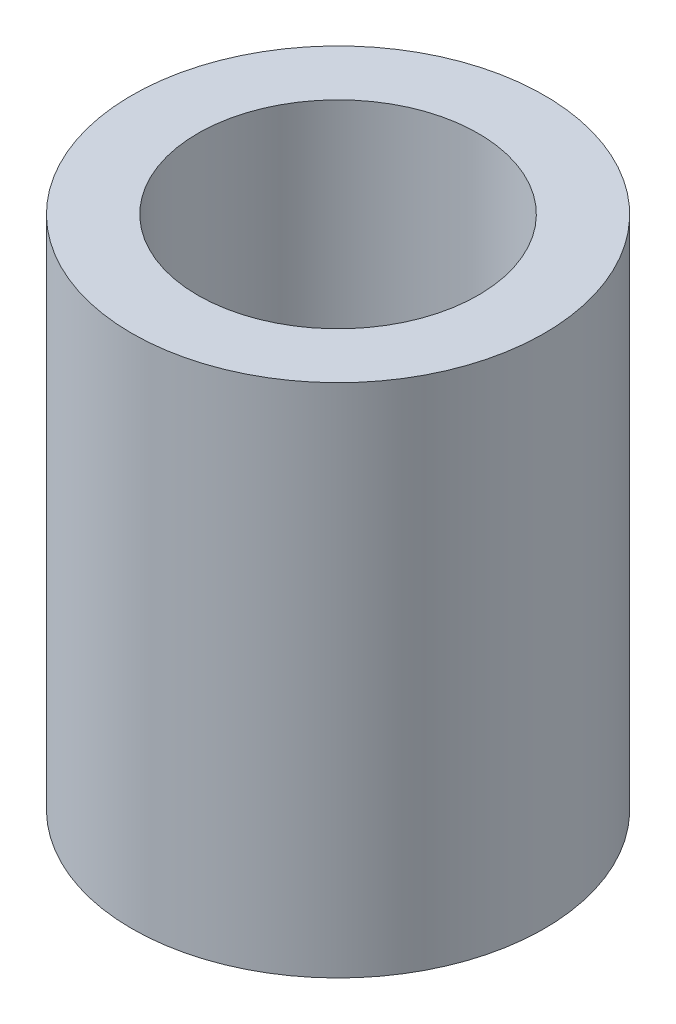
SolidWorks part; units mm, degrees
ref_plane "Front Plane" through (0, 0, 0) normal (0, 0, 1) x (1, 0, 0)
ref_plane "Top Plane" through (0, 0, 0) normal (0, 1, 0) x (1, 0, 0)
ref_plane "Right Plane" through (0, 0, 0) normal (1, 0, 0) x (0, 0, -1)
sketch "Sketch1" plane through (0, 0, 0) normal (0, 1, 0) x (1, 0, 0)
  circle A0 centre (0, 0) radius 1.7
  circle A1 centre (0, 0) radius 2.5
  dimension "D1" = 3.4
  dimension "D2" = 5
extrude "Boss-Extrude1" add sketch "Sketch1" along normal blind 6.25
